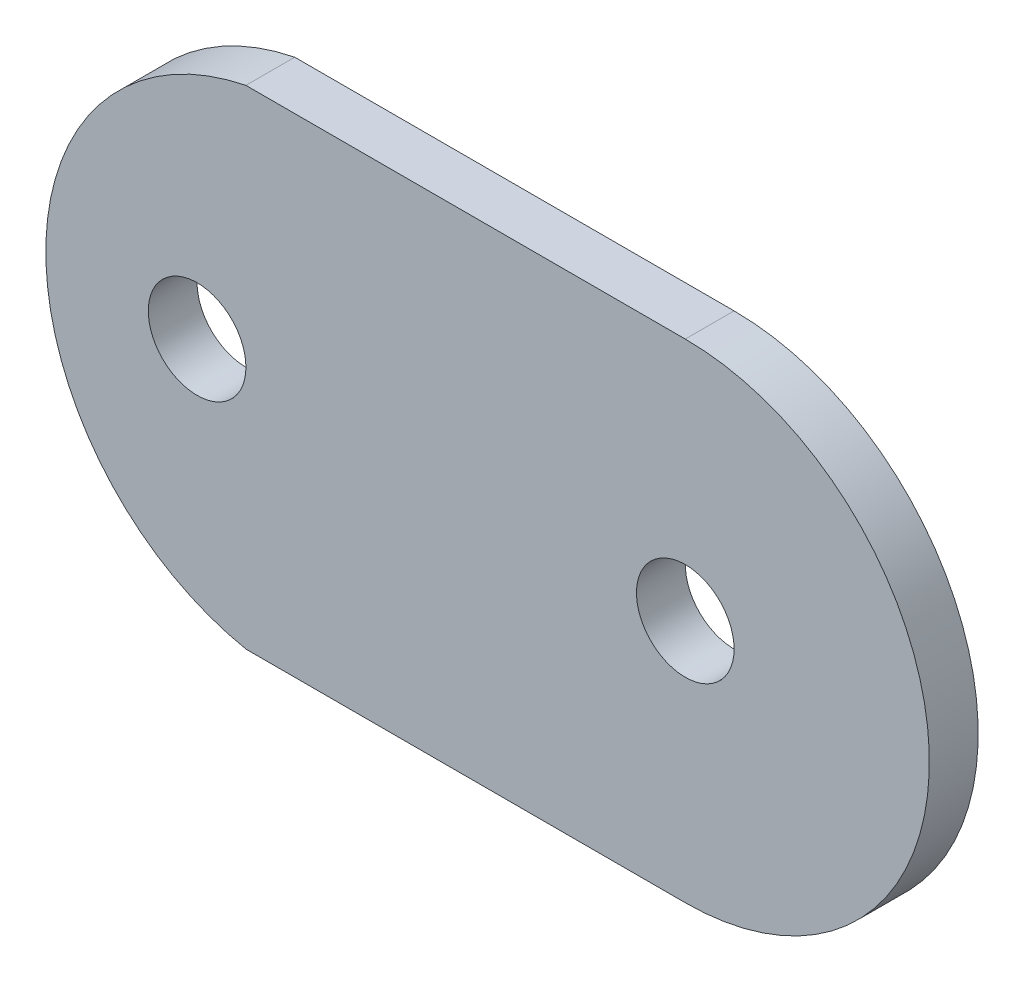
SolidWorks part; units mm, degrees
material "Stainless Steel (ferritic)"
ref_plane "Front Plane" through (0, 0, 0) normal (0, 0, 1) x (1, 0, 0)
ref_plane "Top Plane" through (0, 0, 0) normal (0, 1, 0) x (1, 0, 0)
ref_plane "Right Plane" through (0, 0, 0) normal (1, 0, 0) x (0, 0, -1)
sketch "Sketch6" plane through (0, 0, 0) normal (0, 0, 1) x (1, 0, 0)
  line L0 (0, 10) -> (-3, 10)
  line L1 (0, 0) -> (5, 0)
  line L3 (0, 10) -> (5, 10)
  line L5 (-3, 10) -> (-4, 10)
  line L6 (-3, 10) -> (-3, 0) construction
  line L7 (-3, 0) -> (0, 0)
  line L8 (-4, 10) -> (-4, 0) construction
  line L9 (-3, 0) -> (-4, 0)
  arc A0 (5, 10) -> (5, 0) centre (5, 5) cw
  arc A1 (-4, 10) -> (-4, 0) centre (-3, 5) ccw
  circle A2 centre (5, 5) radius 1
  circle A3 centre (-5, 5) radius 1
  point P14 (0, 0)
  point P15 (-3.8503, 5)
  point P16 (5, 5)
  dimension "D3" = 5
  dimension "D6" = 2
  dimension "D7" = 2
  dimension "D9" = 5.099
  dimension "D1" = 10
  dimension "D2" = 5
  dimension "D4" = 3
  dimension "D5" = 1
  dimension "D8" = 2
extrude "Boss-Extrude4" add sketch "Sketch6" along normal blind 1
